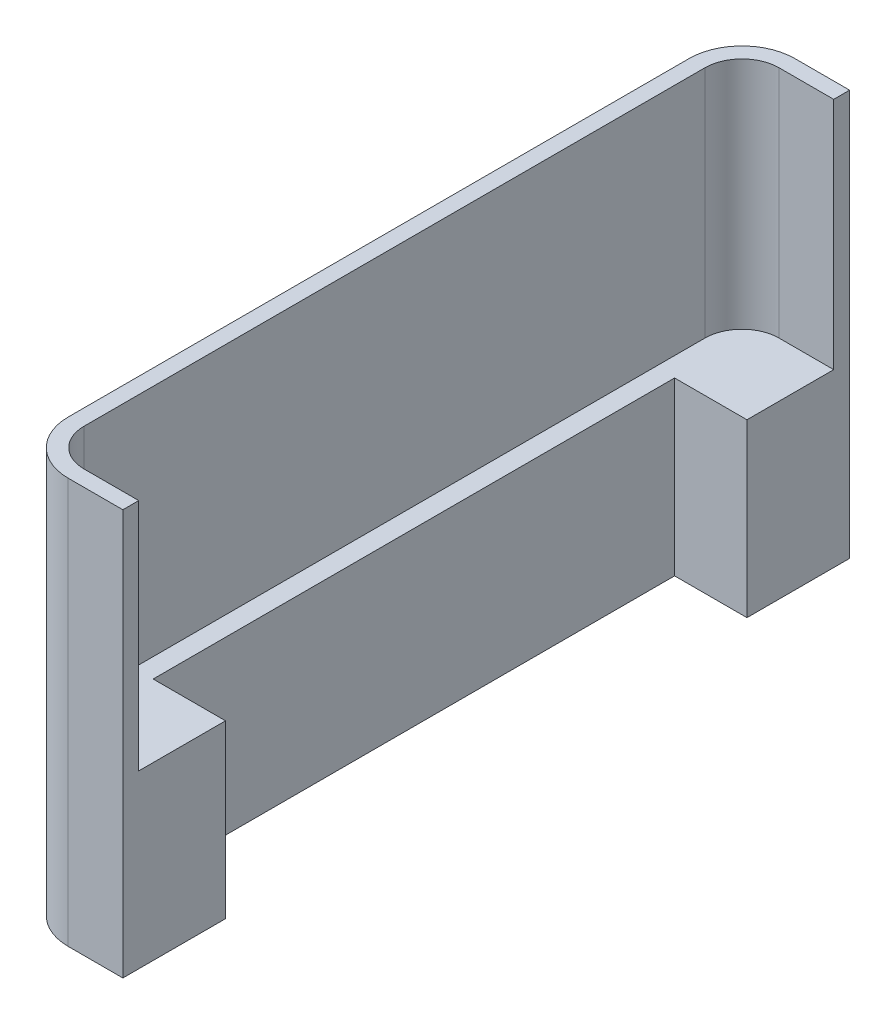
SolidWorks part; units mm, degrees
ref_plane "Front Plane" through (0, 0, 0) normal (0, 0, 1) x (1, 0, 0)
ref_plane "Top Plane" through (0, 0, 0) normal (0, 1, 0) x (1, 0, 0)
ref_plane "Right Plane" through (0, 0, 0) normal (1, 0, 0) x (0, 0, -1)
sketch "Sketch1" plane through (0, 1.61, 0) normal (0, 1, 0) x (1, 0, 0)
  line L0 (-46.865, 18.735) -> (-46.865, -6.665) construction
  line L1 (-44.325, 18.735) -> (-46.865, 18.735) construction
  line L2 (-45.22, 17.84) -> (-45.97, 17.84) construction
  line L3 (-45.97, -5.77) -> (-45.97, 17.84) construction
  line L4 (-46.865, 18.735) -> (-46.865, -6.665)
  line L5 (-44.325, 18.735) -> (-46.865, 18.735)
  line L6 (-45.22, 17.84) -> (-45.97, 17.84)
  line L7 (-45.97, -5.77) -> (-45.97, 17.84)
sketch "Sketch2" plane through (0, 1.61, 0) normal (0, 1, 0) x (1, 0, 0)
  line L0 (-48.135, 6.035) -> (-46.865, 6.035) construction
  line L1 (-48.135, -11.115) -> (-43.055, -11.115)
  line L2 (-48.135, -11.115) -> (-48.135, 23.185)
  line L3 (-48.135, 23.185) -> (-43.055, 23.185)
  line L4 (-43.055, -11.115) -> (-43.055, 23.185)
  line L5 (-46.865, 18.735) -> (-46.865, -6.665) construction
  line L6 (-45.595, 18.735) -> (-45.595, 23.185) construction
  line L7 (-44.325, 18.735) -> (-46.865, 18.735) construction
  dimension "D1" = 4.45
  dimension "D2" = 1.27
extrude "Boss-Extrude1" add sketch "Sketch2" along normal up to surface (19.1389 mm away)
fillet "Fillet1" radius 2.5 2 edges at (-48.135, 11.1795, 11.115) (-48.135, 11.1795, -23.185)
ref_plane "Plane1" through (0, 9.7, 0) normal (0, -1, 0) x (-1, 0, 0)
sketch "Sketch3" plane through (0, 9.7, 0) normal (0, -1, 0) x (-1, 0, 0)
  line L0 (45.595, 17.84) -> (45.595, 18.34) construction
  line L1 (45.22, 17.84) -> (45.97, 17.84) construction
  line L2 (43.055, -6.27) -> (46.47, -6.27)
  line L3 (43.055, -6.27) -> (43.055, 18.34)
  line L4 (43.055, 18.34) -> (46.47, 18.34)
  line L5 (46.47, -6.27) -> (46.47, 18.34)
  line L6 (45.97, -5.77) -> (45.97, 17.84) construction
  line L7 (45.22, 17.84) -> (45.97, 17.84) construction
  line L8 (45.97, -5.77) -> (45.97, 17.84) construction
  line L9 (46.47, 6.035) -> (45.97, 6.035) construction
  line L10 (43.055, -11.115) -> (43.055, 23.185) construction
  point P11 (0, 0)
  dimension "D1" = 0.5
  dimension "D2" = 0.5
extrude "Cut-Extrude1" cut sketch "Sketch3" along normal through all
sketch "Sketch4" plane through (0, 20.7489, 0) normal (0, 1, 0) x (1, 0, 0)
  line L9 (-43.055, -10.365) -> (-43.055, 22.435)
  line L12 (-43.055, 22.435) -> (-45.635, 22.435)
  line L13 (-47.385, 20.685) -> (-47.385, -8.615)
  line L14 (-45.635, -10.365) -> (-43.055, -10.365)
  line L15 (-43.055, 22.435) -> (-45.635, 22.435)
  line L16 (-47.385, 20.685) -> (-47.385, -8.615)
  line L17 (-45.635, -10.365) -> (-43.055, -10.365)
  arc A8 (-45.635, 22.435) -> (-47.385, 20.685) centre (-45.635, 20.685) ccw
  arc A9 (-47.385, -8.615) -> (-45.635, -10.365) centre (-45.635, -8.615) ccw
  arc A10 (-45.635, 22.435) -> (-47.385, 20.685) centre (-45.635, 20.685) ccw
  arc A11 (-47.385, -8.615) -> (-45.635, -10.365) centre (-45.635, -8.615) ccw
  dimension "D1" = 0.75
extrude "Cut-Extrude2" cut sketch "Sketch4" against normal up to surface (11.0489 mm away) up to face at (-44.7625, 9.7, -6.035)
